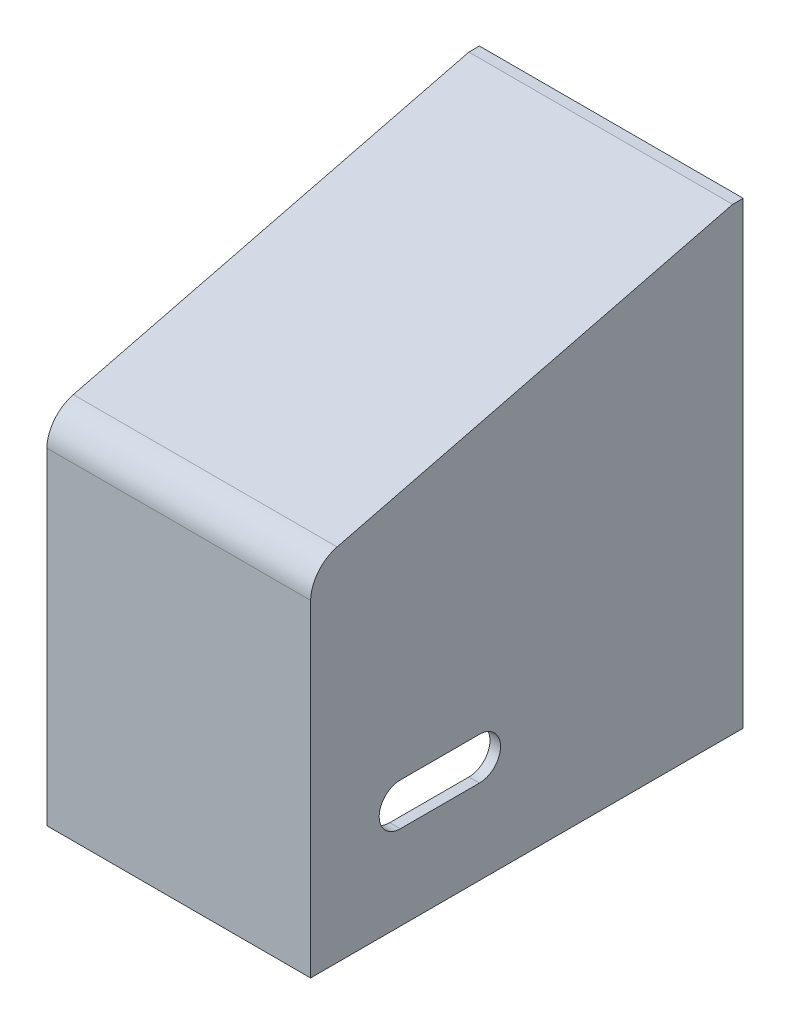
SolidWorks part; units mm, degrees
ref_plane "前视基准面" through (0, 0, 0) normal (0, 0, 1) x (1, 0, 0)
ref_plane "上视基准面" through (0, 0, 0) normal (0, 1, 0) x (1, 0, 0)
ref_plane "右视基准面" through (0, 0, 0) normal (1, 0, 0) x (0, 0, -1)
other "Configuration Table"
ref_plane "基准面1" through (0, 0, 80) normal (0, 0, 1) x (1, 0, 0)
sketch "草图2" plane through (0, 0, 0) normal (0, 0, 1) x (1, 0, 0)
  line L0 (0, 0) -> (0, 85)
  line L1 (0, -55) -> (0, 55) construction
  line L2 (0, 85) -> (46, 85)
  line L3 (46, 85) -> (46, 0)
  line L9 (-2, 87) -> (-2, 0)
  line L10 (-2, 0) -> (0, 0)
  line L12 (48, 0) -> (46, 0)
  line L13 (-2, 87) -> (48, 87)
  line L14 (48, 0) -> (48, 87)
sketch "草图3" plane through (0, 0, 80) normal (0, 0, 1) x (1, 0, 0)
  line L9 (-2, 0) -> (-2, 65)
  line L10 (-2, 65) -> (-2, 67)
  line L13 (-2, 67) -> (48, 67)
  line L14 (48, 67) -> (48, 0)
  line L15 (-2, 0) -> (48, 0)
extrude "凸台-拉伸1" add sketch "草图3" along normal blind 2
extrude "凸台-拉伸2" add sketch "草图2" along normal blind 2 separate body
sketch "草图7" plane through (-2, 0, 0) normal (-1, 0, 0) x (0, 0, 1)
  line L0 (2, 87) -> (82, 67)
  line L1 (82, 67) -> (82, 65)
  line L2 (82, 67) -> (82, 0) construction
  line L3 (82, 65) -> (2, 85)
  line L4 (2, 85) -> (2, 87)
extrude "凸台-拉伸6" add sketch "草图7" against normal blind 50
sketch "草图8" plane through (-2, 0, 0) normal (-1, 0, 0) x (0, 0, 1)
  line L0 (2, 85) -> (80, 65.5)
  line L1 (80, 65.5) -> (80, 0)
  line L2 (82, 0) -> (80, 0) construction
  line L3 (80, 65.5) -> (80, 0) construction
  line L4 (80, 0) -> (2, 0)
  line L5 (2, 0) -> (2, 85)
extrude "凸台-拉伸7" add sketch "草图8" against normal blind 2 separate body
sketch "草图9" plane through (48, 0, 0) normal (1, 0, 0) x (0, 0, -1)
  line L0 (-80, 65.5) -> (-2, 85)
  line L1 (-2, 85) -> (-2, 0)
  line L2 (-2, 0) -> (-80, 0)
  line L3 (-80, 0) -> (-80, 65.5)
extrude "凸台-拉伸8" add sketch "草图9" against normal blind 2
sketch "草图10" plane through (48, 0, 0) normal (1, 0, 0) x (0, 0, -1)
  line L0 (-82, 67) -> (-76.9735, 68.2566)
  line L3 (-82, 67) -> (-2, 87) construction
  line L5 (-82, 67) -> (-82, 62)
  line L6 (-82, 0) -> (-82, 67) construction
  arc A0 (-76.9735, 68.2566) -> (-82, 62) centre (-75.3632, 61.8155) ccw
extrude "切除-拉伸1" cut sketch "草图10" against normal through all
sketch "草图11" plane through (-2, 0, 0) normal (-1, 0, 0) x (0, 0, 1)
  line L0 (0, 0) -> (82, 0) construction
  line L1 (82, 0) -> (82, 40) construction
  line L2 (82, 62) -> (82, 0) construction
  line L3 (82, 40) -> (0, 40) construction
  line L4 (0, 87) -> (0, 0) construction
  line L5 (0, 40) -> (0, 0) construction
  line L6 (0, 20) -> (82, 20) construction
  line L7 (50, 24) -> (65, 24)
  line L8 (50, 16) -> (65, 16)
  arc A0 (65, 16) -> (65, 24) centre (65, 20) ccw
  arc A1 (50, 24) -> (50, 16) centre (50, 20) ccw
  dimension "D1" = 17
  dimension "D2" = 15
extrude "切除-拉伸2" cut sketch "草图11" against normal through all
